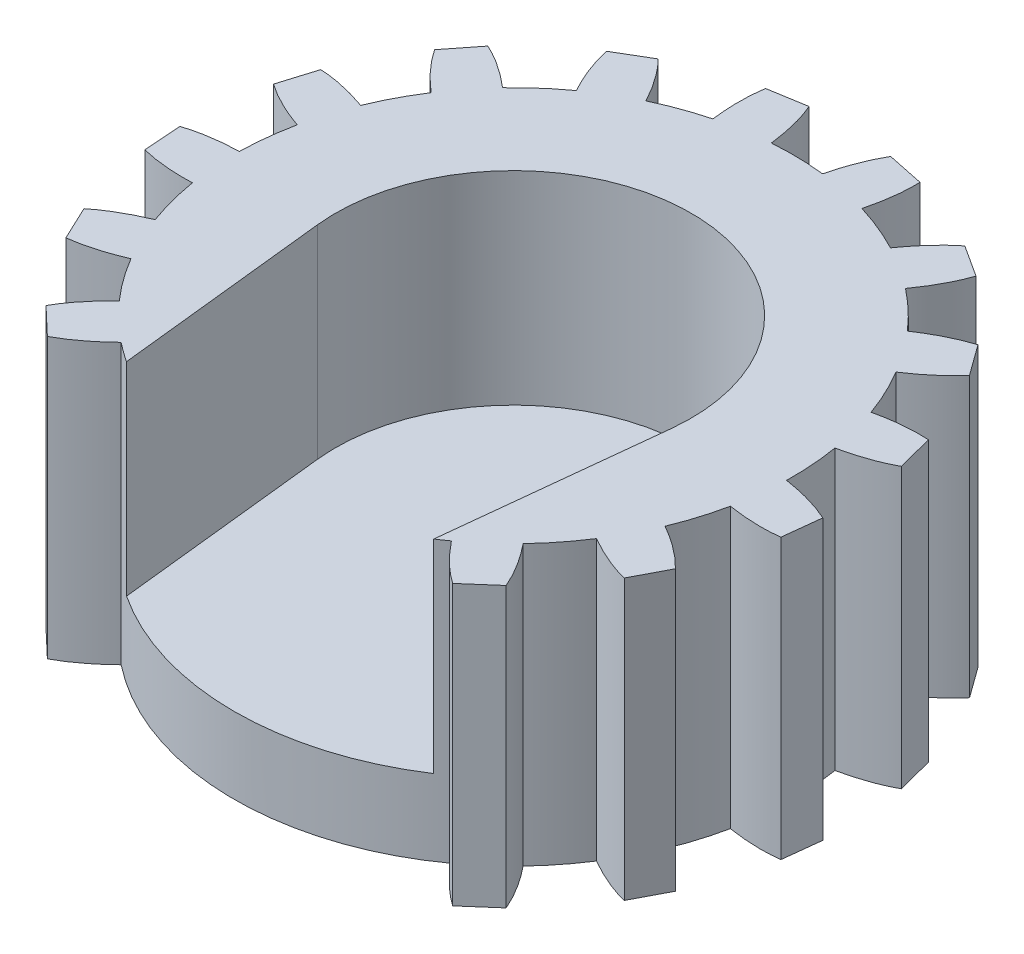
SolidWorks part; units mm, degrees
ref_plane "前视基准面" through (0, 0, 0) normal (0, 0, 1) x (1, 0, 0)
ref_plane "上视基准面" through (0, 0, 0) normal (0, 1, 0) x (1, 0, 0)
ref_plane "右视基准面" through (0, 0, 0) normal (1, 0, 0) x (0, 0, -1)
other "Configuration Table"
sketch "草图1" plane through (0, 0, 0) normal (0, 1, 0) x (1, 0, 0)
  line L0 (0, 0) -> (0, -14)
  line L1 (-1.9885, -14.2143) -> (-3.4799, -0.375)
  line L2 (3.4799, -0.375) -> (1.9885, -14.2143)
  line L3 (1.8359, -6.249) -> (2.5364, -5.9939)
  line L4 (3.6218, -4.1392) -> (4.2803, -4.8918)
  line L5 (3.9693, -5.1639) -> (4.5303, -4.6729)
  line L6 (-0.5455, -6.4902) -> (0.1998, -6.5054)
  line L7 (-2.8532, -5.8549) -> (-2.1637, -6.1383)
  line L8 (-4.7756, -4.4288) -> (-4.235, -4.9422)
  line L9 (-6.053, -2.4046) -> (-5.7343, -3.0786)
  line L10 (-6.5129, -0.0557) -> (-6.4592, -0.7992)
  line L11 (-6.0932, 2.3008) -> (-6.3118, 1.5881)
  line L12 (-4.8506, 4.3466) -> (-5.3119, 3.7609)
  line L13 (-2.9529, 5.8053) -> (-3.5946, 5.4258)
  line L14 (-0.6564, 6.48) -> (-1.3918, 6.3579)
  line L15 (1.7288, 6.2795) -> (0.9989, 6.4314)
  line L16 (3.8805, 5.2309) -> (3.2548, 5.6362)
  line L17 (5.5081, 3.4759) -> (5.071, 4.0799)
  line L18 (6.3918, 1.2514) -> (6.2024, 1.9725)
  line L19 (6.4122, -1.142) -> (6.4961, -0.4013)
  line L20 (5.5667, -3.3813) -> (5.9125, -2.7208)
  circle A0 centre (0, 0) radius 3.5
  arc A1 (-3.4081, -4.3168) -> (3.2309, -4.451) centre (0, 0) ccw
  circle A2 centre (0, -14) radius 2
  arc A3 (-4.7373, -2.7942) -> (-4.1339, -3.6278) centre (0, 0) ccw
  arc A4 (-5.4268, -0.8942) -> (-5.1653, -1.8895) centre (0, 0) ccw
  arc A5 (-5.3834, 1.1266) -> (-5.499, 0.104) centre (0, 0) ccw
  arc A6 (-4.6129, 2.9952) -> (-5.0901, 2.0835) centre (0, 0) ccw
  arc A7 (-3.2194, 4.4593) -> (-3.9937, 3.7815) centre (0, 0) ccw
  arc A8 (-1.3911, 5.3212) -> (-2.358, 4.9689) centre (0, 0) ccw
  arc A9 (0.6251, 5.4644) -> (-0.4038, 5.4852) centre (0, 0) ccw
  arc A10 (2.5568, 4.8696) -> (1.6049, 5.2606) centre (0, 0) ccw
  arc A11 (4.1433, 3.6171) -> (3.3969, 4.3256) centre (0, 0) ccw
  arc A12 (5.1701, 1.8761) -> (4.7301, 2.8064) centre (0, 0) ccw
  arc A13 (5.4987, -0.1182) -> (5.4245, 0.9082) centre (0, 0) ccw
  arc A14 (5.0847, -2.0966) -> (5.3863, -1.1127) centre (0, 0) ccw
  arc A15 (3.984, -3.7918) -> (4.6206, -2.9833) centre (0, 0) ccw
  ellipse E0 centre (3.6218, -4.1392) end of major axis (2.6863, -2.9666) minor radius 0.5 (3.2309, -4.451) -> (3.9693, -5.1639) ccw
  ellipse E1 centre (3.6218, -4.1392) end of major axis (4.5572, -5.3118) minor radius 0.5 (4.5303, -4.6729) -> (3.984, -3.7918) ccw
  ellipse E2 centre (1.8819, -5.168) end of major axis (1.4333, -3.7367) minor radius 0.5 (1.4048, -5.3176) -> (1.8359, -6.249) ccw
  ellipse E3 centre (1.8819, -5.168) end of major axis (1.4333, -3.7367) minor radius 0.5 (2.5364, -5.9939) -> (2.3452, -4.975) ccw
  ellipse E4 centre (-0.112, -5.4989) end of major axis (-0.2107, -6.9956) minor radius 0.5 (-0.611, -5.466) -> (-0.5455, -6.4902) ccw
  ellipse E5 centre (-0.112, -5.4989) end of major axis (-0.2107, -6.9956) minor radius 0.5 (0.1998, -6.5054) -> (0.3896, -5.4862) ccw
  ellipse E6 centre (-2.0909, -5.0871) end of major axis (-2.7236, -6.4471) minor radius 0.5 (-2.5442, -4.8762) -> (-2.8532, -5.8549) ccw
  ellipse E7 centre (-2.0909, -5.0871) end of major axis (-2.7236, -6.4471) minor radius 0.5 (-2.1637, -6.1383) -> (-1.6185, -5.2565) ccw
  ellipse E8 centre (-3.7874, -3.9882) end of major axis (-2.7061, -2.9486) minor radius 0.5 (-4.1339, -3.6278) -> (-4.7756, -4.4288) ccw
  ellipse E9 centre (-3.7874, -3.9882) end of major axis (-4.8686, -5.0278) minor radius 0.5 (-4.235, -4.9422) -> (-3.4081, -4.3168) ccw
  ellipse E10 centre (-4.9723, -2.3508) end of major axis (-6.3561, -2.9296) minor radius 0.5 (-5.1653, -1.8895) -> (-6.053, -2.4046) ccw
  ellipse E11 centre (-4.9723, -2.3508) end of major axis (-3.5885, -1.7719) minor radius 0.5 (-5.7343, -3.0786) -> (-4.7373, -2.7942) ccw
  ellipse E12 centre (-5.4857, -0.3958) end of major axis (-6.9852, -0.4356) minor radius 0.5 (-5.499, 0.104) -> (-6.5129, -0.0557) ccw
  ellipse E13 centre (-5.4857, -0.3958) end of major axis (-6.9852, -0.4356) minor radius 0.5 (-6.4592, -0.7992) -> (-5.4268, -0.8942) ccw
  ellipse E14 centre (-5.2583, 1.6126) end of major axis (-6.6709, 2.1171) minor radius 0.5 (-5.0901, 2.0835) -> (-6.0932, 2.3008) ccw
  ellipse E15 centre (-5.2583, 1.6126) end of major axis (-6.6709, 2.1171) minor radius 0.5 (-6.3118, 1.5881) -> (-5.3834, 1.1266) ccw
  ellipse E16 centre (-4.3207, 3.4032) end of major axis (-5.4556, 4.384) minor radius 0.5 (-3.9937, 3.7815) -> (-4.8506, 4.3466) ccw
  ellipse E17 centre (-4.3207, 3.4032) end of major axis (-5.4556, 4.384) minor radius 0.5 (-5.3119, 3.7609) -> (-4.6129, 2.9952) ccw
  ellipse E18 centre (-2.7995, 4.7342) end of major axis (-3.5035, 6.0587) minor radius 0.5 (-2.358, 4.9689) -> (-2.9529, 5.8053) ccw
  ellipse E19 centre (-2.7995, 4.7342) end of major axis (-3.5035, 6.0587) minor radius 0.5 (-3.5946, 5.4258) -> (-3.2194, 4.4593) ccw
  ellipse E20 centre (-0.9003, 5.4258) end of major axis (-1.0783, 6.9152) minor radius 0.5 (-0.4038, 5.4852) -> (-0.6564, 6.48) ccw
  ellipse E21 centre (-0.9003, 5.4258) end of major axis (-1.0783, 6.9152) minor radius 0.5 (-1.3918, 6.3579) -> (-1.3911, 5.3212) ccw
  ellipse E22 centre (1.1206, 5.3846) end of major axis (1.4926, 6.8378) minor radius 0.5 (1.6049, 5.2606) -> (1.7288, 6.2795) ccw
  ellipse E23 centre (1.1206, 5.3846) end of major axis (1.4926, 6.8378) minor radius 0.5 (0.9989, 6.4314) -> (0.6251, 5.4644) ccw
  ellipse E24 centre (2.99, 4.6162) end of major axis (3.8619, 5.8368) minor radius 0.5 (3.3969, 4.3256) -> (3.8805, 5.2309) ccw
  ellipse E25 centre (2.99, 4.6162) end of major axis (3.8619, 5.8368) minor radius 0.5 (3.2548, 5.6362) -> (2.5568, 4.8696) ccw
  ellipse E26 centre (4.4557, 3.2244) end of major axis (3.2018, 2.4012) minor radius 0.5 (4.7301, 2.8064) -> (5.5081, 3.4759) ccw
  ellipse E27 centre (4.4557, 3.2244) end of major axis (3.2018, 2.4012) minor radius 0.5 (5.071, 4.0799) -> (4.1433, 3.6171) ccw
  ellipse E28 centre (5.3196, 1.3971) end of major axis (6.7862, 1.7117) minor radius 0.5 (5.4245, 0.9082) -> (6.3918, 1.2514) ccw
  ellipse E29 centre (5.3196, 1.3971) end of major axis (6.7862, 1.7117) minor radius 0.5 (6.2024, 1.9725) -> (5.1701, 1.8761) ccw
  ellipse E30 centre (5.4651, -0.6189) end of major axis (6.9463, -0.8553) minor radius 0.5 (5.3863, -1.1127) -> (6.4122, -1.142) ccw
  ellipse E31 centre (5.4651, -0.6189) end of major axis (6.9463, -0.8553) minor radius 0.5 (6.4961, -0.4013) -> (5.4987, -0.1182) ccw
  ellipse E32 centre (4.8724, -2.5514) end of major axis (6.1683, -3.3069) minor radius 0.5 (4.6206, -2.9833) -> (5.5667, -3.3813) ccw
  ellipse E33 centre (4.8724, -2.5514) end of major axis (6.1683, -3.3069) minor radius 0.5 (5.9125, -2.7208) -> (5.0847, -2.0966) ccw
  point P235 (0, 0)
  dimension "D1" = 17
extrude "凸台-拉伸1" add sketch "草图1" along normal blind 5.5
sketch "草图2" plane through (0, 5.5, 0) normal (0, 1, 0) x (1, 0, 0)
  line L0 (3.6218, -4.1392) -> (4.2803, -4.8918) construction
  line L1 (3.4799, -0.375) -> (1.9885, -14.2143) construction
  line L2 (-1.9885, -14.2143) -> (-3.4799, -0.375) construction
  line L3 (0, 0) -> (0, -14) construction
  line L4 (1.8359, -6.249) -> (2.5364, -5.9939) construction
  line L5 (-0.5455, -6.4902) -> (0.1998, -6.5054) construction
  line L6 (-2.8532, -5.8549) -> (-2.1637, -6.1383) construction
  line L7 (3.6218, -4.1392) -> (4.2803, -4.8918)
  line L8 (3.4799, -0.375) -> (1.9885, -14.2143)
  line L9 (-1.9885, -14.2143) -> (-3.4799, -0.375)
  line L10 (0, 0) -> (0, -14)
  line L11 (1.8359, -6.249) -> (2.5364, -5.9939)
  line L12 (-0.5455, -6.4902) -> (0.1998, -6.5054)
  line L13 (-2.8532, -5.8549) -> (-2.1637, -6.1383)
  line L14 (5.5667, -3.3813) -> (5.9125, -2.7208)
  line L15 (6.4122, -1.142) -> (6.4961, -0.4013)
  line L16 (6.3918, 1.2514) -> (6.2024, 1.9725)
  line L17 (5.5081, 3.4759) -> (5.071, 4.0799)
  line L18 (3.8805, 5.2309) -> (3.2548, 5.6362)
  line L19 (1.7288, 6.2795) -> (0.9989, 6.4314)
  line L20 (-0.6564, 6.48) -> (-1.3918, 6.3579)
  line L21 (-2.9529, 5.8053) -> (-3.5946, 5.4258)
  line L22 (-4.8506, 4.3466) -> (-5.3119, 3.7609)
  line L23 (-6.0932, 2.3008) -> (-6.3118, 1.5881)
  line L24 (-6.5129, -0.0557) -> (-6.4592, -0.7992)
  line L25 (-6.053, -2.4046) -> (-5.7343, -3.0786)
  line L26 (-4.7756, -4.4288) -> (-4.235, -4.9422)
  line L27 (3.9693, -5.1639) -> (4.5303, -4.6729)
  line L28 (5.5667, -3.3813) -> (5.9125, -2.7208)
  line L29 (6.4122, -1.142) -> (6.4961, -0.4013)
  line L30 (6.3918, 1.2514) -> (6.2024, 1.9725)
  line L31 (5.5081, 3.4759) -> (5.071, 4.0799)
  line L32 (3.8805, 5.2309) -> (3.2548, 5.6362)
  line L33 (1.7288, 6.2795) -> (0.9989, 6.4314)
  line L34 (-0.6564, 6.48) -> (-1.3918, 6.3579)
  line L35 (-2.9529, 5.8053) -> (-3.5946, 5.4258)
  line L36 (-4.8506, 4.3466) -> (-5.3119, 3.7609)
  line L37 (-6.0932, 2.3008) -> (-6.3118, 1.5881)
  line L38 (-6.5129, -0.0557) -> (-6.4592, -0.7992)
  line L39 (-6.053, -2.4046) -> (-5.7343, -3.0786)
  line L40 (-4.7756, -4.4288) -> (-4.235, -4.9422)
  line L41 (3.9693, -5.1639) -> (4.5303, -4.6729)
  circle A1 centre (0, -14) radius 2
  circle A2 centre (0, -14) radius 2
  circle A3 centre (0, 0) radius 3.5
  circle A4 centre (0, 0) radius 3.5
  arc A18 (5.0847, -2.0966) -> (5.3863, -1.1127) centre (0, 0) ccw
  arc A19 (5.4987, -0.1182) -> (5.4245, 0.9082) centre (0, 0) ccw
  arc A20 (5.1701, 1.8761) -> (4.7301, 2.8064) centre (0, 0) ccw
  arc A21 (4.1433, 3.6171) -> (3.3969, 4.3256) centre (0, 0) ccw
  arc A22 (2.5568, 4.8696) -> (1.6049, 5.2606) centre (0, 0) ccw
  arc A23 (0.6251, 5.4644) -> (-0.4038, 5.4852) centre (0, 0) ccw
  arc A24 (-1.3911, 5.3212) -> (-2.358, 4.9689) centre (0, 0) ccw
  arc A25 (-3.2194, 4.4593) -> (-3.9937, 3.7815) centre (0, 0) ccw
  arc A26 (-4.6129, 2.9952) -> (-5.0901, 2.0835) centre (0, 0) ccw
  arc A27 (-5.3834, 1.1266) -> (-5.499, 0.104) centre (0, 0) ccw
  arc A28 (-5.4268, -0.8942) -> (-5.1653, -1.8895) centre (0, 0) ccw
  arc A29 (-4.7373, -2.7942) -> (-4.1339, -3.6278) centre (0, 0) ccw
  arc A30 (-3.4081, -4.3168) -> (3.2309, -4.451) centre (0, 0) ccw
  arc A31 (3.984, -3.7918) -> (4.6206, -2.9833) centre (0, 0) ccw
  arc A32 (5.0847, -2.0966) -> (5.3863, -1.1127) centre (0, 0) ccw
  arc A33 (5.4987, -0.1182) -> (5.4245, 0.9082) centre (0, 0) ccw
  arc A34 (5.1701, 1.8761) -> (4.7301, 2.8064) centre (0, 0) ccw
  arc A35 (4.1433, 3.6171) -> (3.3969, 4.3256) centre (0, 0) ccw
  arc A36 (2.5568, 4.8696) -> (1.6049, 5.2606) centre (0, 0) ccw
  arc A37 (0.6251, 5.4644) -> (-0.4038, 5.4852) centre (0, 0) ccw
  arc A38 (-1.3911, 5.3212) -> (-2.358, 4.9689) centre (0, 0) ccw
  arc A39 (-3.2194, 4.4593) -> (-3.9937, 3.7815) centre (0, 0) ccw
  arc A40 (-4.6129, 2.9952) -> (-5.0901, 2.0835) centre (0, 0) ccw
  arc A41 (-5.3834, 1.1266) -> (-5.499, 0.104) centre (0, 0) ccw
  arc A42 (-5.4268, -0.8942) -> (-5.1653, -1.8895) centre (0, 0) ccw
  arc A43 (-4.7373, -2.7942) -> (-4.1339, -3.6278) centre (0, 0) ccw
  arc A44 (-3.4081, -4.3168) -> (3.2309, -4.451) centre (0, 0) ccw
  arc A45 (3.984, -3.7918) -> (4.6206, -2.9833) centre (0, 0) ccw
  ellipse E0 centre (1.8819, -5.168) end of major axis (2.3306, -6.5993) minor radius 0.5 (2.5364, -5.9939) -> (2.3452, -4.975) ccw construction
  ellipse E1 centre (1.8819, -5.168) end of major axis (2.3306, -6.5993) minor radius 0.5 (1.4048, -5.3176) -> (1.8359, -6.249) ccw construction
  ellipse E2 centre (-0.112, -5.4989) end of major axis (-0.2107, -6.9956) minor radius 0.5 (-0.611, -5.466) -> (-0.5455, -6.4902) ccw construction
  ellipse E3 centre (-0.112, -5.4989) end of major axis (-0.2107, -6.9956) minor radius 0.5 (0.1998, -6.5054) -> (0.3896, -5.4862) ccw construction
  ellipse E4 centre (-2.0909, -5.0871) end of major axis (-2.7236, -6.4471) minor radius 0.5 (-2.5442, -4.8762) -> (-2.8532, -5.8549) ccw construction
  ellipse E5 centre (-2.0909, -5.0871) end of major axis (-2.7236, -6.4471) minor radius 0.5 (-2.1637, -6.1383) -> (-1.6185, -5.2565) ccw construction
  ellipse E6 centre (1.8819, -5.168) end of major axis (2.3306, -6.5993) minor radius 0.5 (2.5364, -5.9939) -> (2.3452, -4.975) ccw
  ellipse E7 centre (1.8819, -5.168) end of major axis (2.3306, -6.5993) minor radius 0.5 (1.4048, -5.3176) -> (1.8359, -6.249) ccw
  ellipse E8 centre (-0.112, -5.4989) end of major axis (-0.2107, -6.9956) minor radius 0.5 (-0.611, -5.466) -> (-0.5455, -6.4902) ccw
  ellipse E9 centre (-0.112, -5.4989) end of major axis (-0.2107, -6.9956) minor radius 0.5 (0.1998, -6.5054) -> (0.3896, -5.4862) ccw
  ellipse E10 centre (-2.0909, -5.0871) end of major axis (-2.7236, -6.4471) minor radius 0.5 (-2.5442, -4.8762) -> (-2.8532, -5.8549) ccw
  ellipse E11 centre (-2.0909, -5.0871) end of major axis (-2.7236, -6.4471) minor radius 0.5 (-2.1637, -6.1383) -> (-1.6185, -5.2565) ccw
  ellipse E28 centre (4.8724, -2.5514) end of major axis (6.1683, -3.3069) minor radius 0.5 (5.9125, -2.7208) -> (5.0847, -2.0966) ccw
  ellipse E29 centre (5.4651, -0.6189) end of major axis (6.9463, -0.8553) minor radius 0.5 (5.3863, -1.1127) -> (6.4122, -1.142) ccw
  ellipse E30 centre (5.4651, -0.6189) end of major axis (6.9463, -0.8553) minor radius 0.5 (6.4961, -0.4013) -> (5.4987, -0.1182) ccw
  ellipse E31 centre (5.3196, 1.3971) end of major axis (6.7862, 1.7117) minor radius 0.5 (5.4245, 0.9082) -> (6.3918, 1.2514) ccw
  ellipse E32 centre (5.3196, 1.3971) end of major axis (6.7862, 1.7117) minor radius 0.5 (6.2024, 1.9725) -> (5.1701, 1.8761) ccw
  ellipse E33 centre (4.4557, 3.2244) end of major axis (5.7096, 4.0476) minor radius 0.5 (4.7301, 2.8064) -> (5.5081, 3.4759) ccw
  ellipse E34 centre (4.4557, 3.2244) end of major axis (5.7096, 4.0476) minor radius 0.5 (5.071, 4.0799) -> (4.1433, 3.6171) ccw
  ellipse E35 centre (2.99, 4.6162) end of major axis (3.8619, 5.8368) minor radius 0.5 (3.3969, 4.3256) -> (3.8805, 5.2309) ccw
  ellipse E36 centre (2.99, 4.6162) end of major axis (3.8619, 5.8368) minor radius 0.5 (3.2548, 5.6362) -> (2.5568, 4.8696) ccw
  ellipse E37 centre (1.1206, 5.3846) end of major axis (1.4926, 6.8378) minor radius 0.5 (1.6049, 5.2606) -> (1.7288, 6.2795) ccw
  ellipse E38 centre (1.1206, 5.3846) end of major axis (1.4926, 6.8378) minor radius 0.5 (0.9989, 6.4314) -> (0.6251, 5.4644) ccw
  ellipse E39 centre (-0.9003, 5.4258) end of major axis (-1.0783, 6.9152) minor radius 0.5 (-0.4038, 5.4852) -> (-0.6564, 6.48) ccw
  ellipse E40 centre (-0.9003, 5.4258) end of major axis (-1.0783, 6.9152) minor radius 0.5 (-1.3918, 6.3579) -> (-1.3911, 5.3212) ccw
  ellipse E41 centre (-2.7995, 4.7342) end of major axis (-3.5035, 6.0587) minor radius 0.5 (-2.358, 4.9689) -> (-2.9529, 5.8053) ccw
  ellipse E42 centre (-2.7995, 4.7342) end of major axis (-3.5035, 6.0587) minor radius 0.5 (-3.5946, 5.4258) -> (-3.2194, 4.4593) ccw
  ellipse E43 centre (-4.3207, 3.4032) end of major axis (-5.4556, 4.384) minor radius 0.5 (-3.9937, 3.7815) -> (-4.8506, 4.3466) ccw
  ellipse E44 centre (-4.3207, 3.4032) end of major axis (-5.4556, 4.384) minor radius 0.5 (-5.3119, 3.7609) -> (-4.6129, 2.9952) ccw
  ellipse E45 centre (-5.2583, 1.6126) end of major axis (-6.6709, 2.1171) minor radius 0.5 (-5.0901, 2.0835) -> (-6.0932, 2.3008) ccw
  ellipse E46 centre (-5.2583, 1.6126) end of major axis (-6.6709, 2.1171) minor radius 0.5 (-6.3118, 1.5881) -> (-5.3834, 1.1266) ccw
  ellipse E47 centre (-5.4857, -0.3958) end of major axis (-6.9852, -0.4356) minor radius 0.5 (-5.499, 0.104) -> (-6.5129, -0.0557) ccw
  ellipse E48 centre (-5.4857, -0.3958) end of major axis (-6.9852, -0.4356) minor radius 0.5 (-6.4592, -0.7992) -> (-5.4268, -0.8942) ccw
  ellipse E49 centre (-4.9723, -2.3508) end of major axis (-6.3561, -2.9296) minor radius 0.5 (-5.1653, -1.8895) -> (-6.053, -2.4046) ccw
  ellipse E50 centre (-4.9723, -2.3508) end of major axis (-6.3561, -2.9296) minor radius 0.5 (-5.7343, -3.0786) -> (-4.7373, -2.7942) ccw
  ellipse E51 centre (-3.7874, -3.9882) end of major axis (-4.8686, -5.0278) minor radius 0.5 (-4.1339, -3.6278) -> (-4.7756, -4.4288) ccw
  ellipse E52 centre (-3.7874, -3.9882) end of major axis (-4.8686, -5.0278) minor radius 0.5 (-4.235, -4.9422) -> (-3.4081, -4.3168) ccw
  ellipse E53 centre (3.6218, -4.1392) end of major axis (4.5572, -5.3118) minor radius 0.5 (3.2309, -4.451) -> (3.9693, -5.1639) ccw
  ellipse E54 centre (3.6218, -4.1392) end of major axis (4.5572, -5.3118) minor radius 0.5 (4.5303, -4.6729) -> (3.984, -3.7918) ccw
  ellipse E55 centre (4.8724, -2.5514) end of major axis (6.1683, -3.3069) minor radius 0.5 (4.6206, -2.9833) -> (5.5667, -3.3813) ccw
  ellipse E56 centre (4.8724, -2.5514) end of major axis (6.1683, -3.3069) minor radius 0.5 (5.9125, -2.7208) -> (5.0847, -2.0966) ccw
  ellipse E57 centre (5.4651, -0.6189) end of major axis (6.9463, -0.8553) minor radius 0.5 (5.3863, -1.1127) -> (6.4122, -1.142) ccw
  ellipse E58 centre (5.4651, -0.6189) end of major axis (6.9463, -0.8553) minor radius 0.5 (6.4961, -0.4013) -> (5.4987, -0.1182) ccw
  ellipse E59 centre (5.3196, 1.3971) end of major axis (6.7862, 1.7117) minor radius 0.5 (5.4245, 0.9082) -> (6.3918, 1.2514) ccw
  ellipse E60 centre (5.3196, 1.3971) end of major axis (6.7862, 1.7117) minor radius 0.5 (6.2024, 1.9725) -> (5.1701, 1.8761) ccw
  ellipse E61 centre (4.4557, 3.2244) end of major axis (5.7096, 4.0476) minor radius 0.5 (4.7301, 2.8064) -> (5.5081, 3.4759) ccw
  ellipse E62 centre (4.4557, 3.2244) end of major axis (5.7096, 4.0476) minor radius 0.5 (5.071, 4.0799) -> (4.1433, 3.6171) ccw
  ellipse E63 centre (2.99, 4.6162) end of major axis (3.8619, 5.8368) minor radius 0.5 (3.3969, 4.3256) -> (3.8805, 5.2309) ccw
  ellipse E64 centre (2.99, 4.6162) end of major axis (3.8619, 5.8368) minor radius 0.5 (3.2548, 5.6362) -> (2.5568, 4.8696) ccw
  ellipse E65 centre (1.1206, 5.3846) end of major axis (1.4926, 6.8378) minor radius 0.5 (1.6049, 5.2606) -> (1.7288, 6.2795) ccw
  ellipse E66 centre (1.1206, 5.3846) end of major axis (1.4926, 6.8378) minor radius 0.5 (0.9989, 6.4314) -> (0.6251, 5.4644) ccw
  ellipse E67 centre (-0.9003, 5.4258) end of major axis (-1.0783, 6.9152) minor radius 0.5 (-0.4038, 5.4852) -> (-0.6564, 6.48) ccw
  ellipse E68 centre (-0.9003, 5.4258) end of major axis (-1.0783, 6.9152) minor radius 0.5 (-1.3918, 6.3579) -> (-1.3911, 5.3212) ccw
  ellipse E69 centre (-2.7995, 4.7342) end of major axis (-3.5035, 6.0587) minor radius 0.5 (-2.358, 4.9689) -> (-2.9529, 5.8053) ccw
  ellipse E70 centre (-2.7995, 4.7342) end of major axis (-3.5035, 6.0587) minor radius 0.5 (-3.5946, 5.4258) -> (-3.2194, 4.4593) ccw
  ellipse E71 centre (-4.3207, 3.4032) end of major axis (-5.4556, 4.384) minor radius 0.5 (-3.9937, 3.7815) -> (-4.8506, 4.3466) ccw
  ellipse E72 centre (-4.3207, 3.4032) end of major axis (-5.4556, 4.384) minor radius 0.5 (-5.3119, 3.7609) -> (-4.6129, 2.9952) ccw
  ellipse E73 centre (-5.2583, 1.6126) end of major axis (-6.6709, 2.1171) minor radius 0.5 (-5.0901, 2.0835) -> (-6.0932, 2.3008) ccw
  ellipse E74 centre (-5.2583, 1.6126) end of major axis (-6.6709, 2.1171) minor radius 0.5 (-6.3118, 1.5881) -> (-5.3834, 1.1266) ccw
  ellipse E75 centre (-5.4857, -0.3958) end of major axis (-6.9852, -0.4356) minor radius 0.5 (-5.499, 0.104) -> (-6.5129, -0.0557) ccw
  ellipse E76 centre (-5.4857, -0.3958) end of major axis (-6.9852, -0.4356) minor radius 0.5 (-6.4592, -0.7992) -> (-5.4268, -0.8942) ccw
  ellipse E77 centre (-4.9723, -2.3508) end of major axis (-6.3561, -2.9296) minor radius 0.5 (-5.1653, -1.8895) -> (-6.053, -2.4046) ccw
  ellipse E78 centre (-4.9723, -2.3508) end of major axis (-6.3561, -2.9296) minor radius 0.5 (-5.7343, -3.0786) -> (-4.7373, -2.7942) ccw
  ellipse E79 centre (-3.7874, -3.9882) end of major axis (-4.8686, -5.0278) minor radius 0.5 (-4.1339, -3.6278) -> (-4.7756, -4.4288) ccw
  ellipse E80 centre (-3.7874, -3.9882) end of major axis (-4.8686, -5.0278) minor radius 0.5 (-4.235, -4.9422) -> (-3.4081, -4.3168) ccw
  ellipse E81 centre (3.6218, -4.1392) end of major axis (4.5572, -5.3118) minor radius 0.5 (3.2309, -4.451) -> (3.9693, -5.1639) ccw
  ellipse E82 centre (3.6218, -4.1392) end of major axis (4.5572, -5.3118) minor radius 0.5 (4.5303, -4.6729) -> (3.984, -3.7918) ccw
  ellipse E83 centre (4.8724, -2.5514) end of major axis (6.1683, -3.3069) minor radius 0.5 (4.6206, -2.9833) -> (5.5667, -3.3813) ccw
  dimension "D1" = 0
  dimension "D2" = 0
  dimension "D3" = 0
extrude "切除-拉伸1" cut sketch "草图2" against normal blind 4
sketch "草图3" plane through (0, 1.5, 0) normal (0, 1, 0) x (1, 0, 0)
  line L0 (0, 0) -> (0, -14)
  circle A0 centre (0, -14) radius 2
sketch "草图4" plane through (0, 1.5, 0) normal (0, 1, 0) x (1, 0, 0)
  circle A0 centre (0, 0) radius 6
